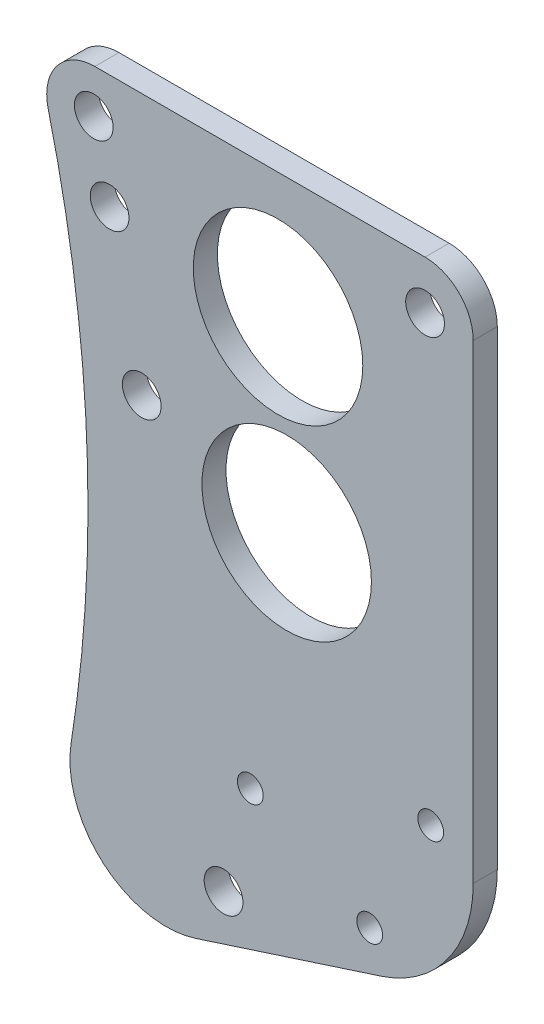
SolidWorks part; units mm, degrees
material "Polypropylene"
ref_plane "Front Plane" through (0, 0, 0) normal (0, 0, 1) x (1, 0, 0)
ref_plane "Top Plane" through (0, 0, 0) normal (0, 1, 0) x (1, 0, 0)
ref_plane "Right Plane" through (0, 0, 0) normal (1, 0, 0) x (0, 0, -1)
sketch "Sketch2" plane through (0, 0, 0) normal (0, 0, 1) x (1, 0, 0)
  line L0 (-139.7, 0) -> (139.7, 0) construction
  line L1 (-139.7, 162.1582) -> (139.7, 162.1582) construction
  line L2 (-139.7, 0) -> (-139.7, 162.1582) construction
  line L3 (89.6578, 156.3951) -> (-88.9, 111.3582) construction
  line L4 (-88.9, 111.3582) -> (87.5277, 58.5898) construction
  line L6 (85.725, 52.9003) -> (82.55, 52.9003) construction
  line L7 (139.7, 162.1582) -> (139.7, 0) construction
  line L8 (-109.7, 30) -> (-102.2692, 59.0652) construction
  line L9 (-102.2692, 59.0652) -> (-101.4828, 62.1412) construction
  line L10 (-101.4828, 62.1412) -> (-88.9, 111.3582) construction
  line L11 (-88.9, 111.3582) -> (85.725, 52.9003) construction
  line L12 (82.55, 52.9003) -> (82.55, 64.2654) construction
  line L13 (-88.9, 111.3582) -> (91.7477, 147.1022) construction
  line L14 (82.55, 52.9003) -> (85.725, 0) construction
  line L15 (85.725, 52.9003) -> (92.4089, 52.9003) construction
  line L16 (-131.5562, 154.0144) -> (-88.9, 111.3582) construction
  line L17 (-88.9, 111.3582) -> (88.9, 111.3582) construction
  line L18 (-88.9, 111.3582) -> (88.1045, 162.1582) construction
  line L22 (82.8416, 162.1582) -> (82.8416, 157.3763) construction
  line L23 (82.8416, 157.3763) -> (-88.9, 111.3582) construction
  line L24 (122.2, 93.8006) -> (115.1001, 121.5451) construction
  line L25 (-88.9, 111.3582) -> (-131.5562, 68.702) construction
  line L26 (120.5994, 121.5451) -> (117.8497, 126.3076) construction
  line L27 (117.8497, 126.3076) -> (112.3505, 126.3076) construction
  line L28 (112.3505, 126.3076) -> (109.6008, 121.5451) construction
  line L29 (109.6008, 121.5451) -> (112.3505, 116.7826) construction
  line L30 (112.3505, 116.7826) -> (117.8497, 116.7826) construction
  line L31 (117.8497, 116.7826) -> (120.5994, 121.5451) construction
  line L40 (-139.7, 154.0144) -> (-139.7, 30) construction
  line L41 (-131.5562, 161.3468) -> (-137.9062, 157.6806) construction
  line L42 (-137.9062, 157.6806) -> (-137.9062, 150.3483) construction
  line L43 (-137.9062, 150.3483) -> (-131.5562, 146.6821) construction
  line L44 (-131.5562, 146.6821) -> (-125.2062, 150.3483) construction
  line L45 (-125.2062, 150.3483) -> (-125.2062, 157.6806) construction
  line L46 (-125.2062, 157.6806) -> (-131.5562, 161.3468) construction
  line L47 (-131.5562, 61.3697) -> (-125.2062, 65.0358) construction
  line L48 (-125.2062, 65.0358) -> (-125.2062, 72.3682) construction
  line L49 (-125.2062, 72.3682) -> (-131.5562, 76.0344) construction
  line L50 (-131.5562, 76.0344) -> (-137.9062, 72.3682) construction
  line L51 (-137.9062, 72.3682) -> (-137.9062, 65.0358) construction
  line L52 (-137.9062, 65.0358) -> (-131.5562, 61.3697) construction
  line L53 (-79.9907, 25.8335) -> (-68.3996, 108.4832) construction
  line L54 (-77.6298, 128.7224) -> (-127.1225, 160.8455) construction
  line L56 (89.8048, 162.1582) -> (133.35, 162.1582)
  line L57 (139.7, 155.8082) -> (139.7, 93.8006)
  line L58 (127.5896, 77.1512) -> (103.1274, 69.2325)
  line L59 (137.8401, 160.2984) -> (129.3001, 151.7583) construction
  line L60 (122.2, 93.8006) -> (110.579, 80.7162) construction
  line L61 (110.579, 80.7162) -> (106.7754, 76.4337) construction
  line L62 (98.6364, 77.8864) -> (101.1368, 77.4401) construction
  line L63 (98.6364, 77.8864) -> (-88.9, 111.3582) construction
  line L64 (106.7754, 76.4337) -> (108.5394, 70.9844) construction
  line L65 (113.9624, 145.6482) -> (95.9884, 127.7012) construction
  line L66 (115.1001, 121.5451) -> (104.4623, 124.9716) construction
  line L67 (95.9884, 127.7012) -> (98.4182, 126.9185) construction
  line L68 (98.4182, 126.9185) -> (104.4623, 124.9716) construction
  line L69 (101.1368, 77.4401) -> (106.7754, 76.4337) construction
  circle A0 centre (-88.9, 111.3582) radius 50.8 construction
  circle A1 centre (-88.9, 111.3582) radius 14.351 construction
  arc A15 (81.4439, 60.4094) -> (81.4884, 162.1582) centre (-88.9, 111.3582) ccw construction
  arc A16 (92.4089, 52.9003) -> (94.7018, 162.1582) centre (-88.9, 111.3582) ccw construction
  arc A17 (89.6578, 156.3951) -> (87.5277, 58.5898) centre (-88.9, 111.3582) cw construction
  arc A18 (90.2045, 57.7892) -> (92.367, 157.0784) centre (-88.9, 111.3582) ccw construction
  arc A19 (84.8508, 59.3905) -> (86.9487, 155.7118) centre (-88.9, 111.3582) ccw construction
  arc A20 (84.8508, 59.3905) -> (90.2045, 57.7892) centre (87.5277, 58.5898) ccw construction
  arc A21 (92.367, 157.0784) -> (86.9487, 155.7118) centre (89.6578, 156.3951) ccw construction
  arc A23 (89.6578, 156.3951) -> (88.1045, 162.1582) centre (-88.9, 111.3582) ccw construction
  circle A24 centre (113.9624, 145.6482) radius 15.24 construction
  circle A25 centre (122.2, 93.8006) radius 17.5 construction
  circle A26 centre (122.2, 93.8006) radius 4.826 construction
  circle A27 centre (115.1001, 121.5451) radius 23.8125 construction
  circle A28 centre (113.9624, 145.6482) radius 16.51 construction
  circle A29 centre (-109.7, 30) radius 30 construction
  circle A30 centre (-109.7, 30) radius 25.4 construction
  circle A31 centre (-109.7, 55.4) radius 2.5527 construction
  circle A32 centre (-97, 51.997) radius 2.5527 construction
  circle A33 centre (-87.703, 42.7) radius 2.5527 construction
  circle A34 centre (-84.3, 30) radius 2.5527 construction
  circle A35 centre (-87.703, 17.3) radius 2.5527 construction
  circle A36 centre (-97, 8.003) radius 2.5527 construction
  circle A37 centre (-109.7, 4.6) radius 2.5527 construction
  circle A38 centre (-122.4, 8.003) radius 2.5527 construction
  circle A39 centre (-131.697, 17.3) radius 2.5527 construction
  circle A40 centre (-135.1, 30) radius 2.5527 construction
  circle A41 centre (-131.697, 42.7) radius 2.5527 construction
  circle A42 centre (-122.4, 51.997) radius 2.5527 construction
  arc A43 (87.5277, 58.5898) -> (85.725, 52.9003) centre (-88.9, 111.3582) cw construction
  circle A44 centre (-109.7, 30) radius 14.351 construction
  circle A48 centre (115.1001, 121.5451) radius 24.5999 construction
  circle A49 centre (122.2, 93.8006) radius 12.5 construction
  circle A50 centre (134.0938, 97.6461) radius 1.25 construction
  circle A51 centre (126.0455, 81.9068) radius 1.25 construction
  circle A52 centre (110.3062, 89.9551) radius 1.25 construction
  circle A53 centre (118.3545, 105.6944) radius 1.25 construction
  circle A54 centre (115.1001, 121.5451) radius 4.7625 construction
  circle A55 centre (115.1001, 121.5451) radius 8.89 construction
  circle A56 centre (115.1001, 121.5451) radius 10.16 construction
  circle A59 centre (113.9624, 145.6482) radius 15.24 construction
  circle A60 centre (113.9624, 145.6482) radius 16.51 construction
  circle A61 centre (89.6578, 156.3951) radius 2.5527
  circle A62 centre (91.7477, 147.1022) radius 2.5527
  circle A63 centre (-131.5562, 68.702) radius 3.175 construction
  circle A64 centre (-131.5562, 154.0144) radius 3.175 construction
  circle A65 centre (-131.5562, 154.0144) radius 6.35 construction
  circle A66 centre (-131.5562, 68.702) radius 6.35 construction
  arc A67 (-139.7, 30) -> (-79.9907, 25.8335) centre (-109.7, 30) ccw construction
  arc A69 (-127.1225, 160.8455) -> (-139.7, 154.0144) centre (-131.5562, 154.0144) ccw construction
  arc A70 (-68.3996, 108.4832) -> (-77.6298, 128.7224) centre (-88.9, 111.3582) ccw construction
  arc A71 (139.7, 93.8006) -> (127.5896, 77.1512) centre (122.2, 93.8006) cw
  arc A72 (83.6426, 154.2755) -> (86.675, 83.318) centre (-88.9, 111.3582) cw
  arc A73 (86.675, 83.318) -> (103.1274, 69.2325) centre (99.2161, 81.3152) ccw
  arc A74 (133.35, 162.1582) -> (139.7, 155.8082) centre (133.35, 155.8082) cw
  circle A76 centre (106.7754, 76.4337) radius 2.5527
  arc A77 (110.3062, 89.9551) -> (134.0938, 97.6461) centre (122.2, 93.8006) ccw construction
  arc A78 (106.0958, 88.5937) -> (138.3042, 99.0075) centre (122.2, 93.8006) ccw construction
  arc A79 (114.5166, 91.3164) -> (129.8834, 96.2848) centre (122.2, 93.8006) ccw construction
  arc A80 (114.5166, 91.3164) -> (106.0958, 88.5937) centre (110.3062, 89.9551) ccw construction
  arc A81 (138.3042, 99.0075) -> (129.8834, 96.2848) centre (134.0938, 97.6461) ccw construction
  circle A82 centre (115.1001, 121.5451) radius 11.176
  arc A83 (83.6426, 154.2755) -> (89.8048, 162.1582) centre (89.8048, 155.8082) cw
  circle A84 centre (113.9624, 145.6482) radius 11.176
  circle A87 centre (133.35, 155.8082) radius 2.5527
  circle A88 centre (95.9884, 127.7012) radius 2.5527
  circle A89 centre (134.0938, 97.6461) radius 1.7
  circle A90 centre (126.0455, 81.9068) radius 1.7
  circle A91 centre (110.3062, 89.9551) radius 1.7
  point P6 (-88.9, 60.5582)
  point P10 (-109.7, 0)
  point P11 (86.727, 55.913)
  point P30 (-88.9, 111.3582)
  point P32 (0, 0)
  point P36 (0, 162.1582)
  point P37 (-88.9, 162.1582)
  point P42 (95.2063, 107.3484)
  point P66 (-109.7, 30)
  point P68 (-139.7, 30)
  point P82 (88.954, 159.099)
  point P85 (-79.7, 30)
  point P92 (88.1045, 162.1582)
  point P105 (122.2, 93.8006)
  point P138 (132.0087, 101.5491)
  point P142 (107.5616, 74.0051)
  point P148 (126.0455, 81.9068)
  point P171 (130.9475, 102.7298)
  dimension "D1" = 101.6
  dimension "D2" = 28.702
  dimension "D3" = 60
  dimension "D4" = 50.8
  dimension "D9" = 127
  dimension "D10" = 12.7
  dimension "D11" = 6.35
  dimension "D12" = 2.794
  dimension "D16" = 35
  dimension "D17" = 9.652
  dimension "D18" = 47.625
  dimension "D19" = 30.48
  dimension "D20" = 30.48
  dimension "D5" = 5.1054
  dimension "D13" = 85.725
  dimension "D25" = 28.702
  dimension "D21" = 82.55
  dimension "D22" = 186.944
  dimension "D30" = 49.1998
  dimension "D31" = 60.325
  dimension "D32" = 27.844
  dimension "D33" = 12.7
  dimension "D34" = 25
  dimension "D35" = 2.5
  dimension "D37" = 9.525
  dimension "D38" = 17.78
  dimension "D39" = 20.32
  dimension "D40" = 6.35
  dimension "D41" = 6.35
  dimension "D42" = 1.27
  dimension "D43" = 1.27
  dimension "D44" = 12.7
  dimension "D45" = 3.175
  dimension "D46" = 3.175
  dimension "D28" = 5.1054
  dimension "D29" = 6.35
  dimension "D47" = 22.352
  dimension "D48" = 6.35
  dimension "D49" = 22.352
  dimension "D52" = 25.4
  dimension "D53" = 5.1054
  dimension "D51" = 5.1054
  dimension "D55" = 2.54
  dimension "D56" = 1.5875
  dimension "D57" = 3.4
  dimension "D6" = 12
  dimension "D7" = 15
  dimension "D8" = 279.4
  dimension "D14" = 3.175
  dimension "D15" = 279.4
  dimension "D23" = 3.175
  dimension "D24" = 3.175
  dimension "D26" = 3.175
  dimension "D27" = 9.525
  dimension "D50" = 12.0774
  dimension "D54" = 6.35
  dimension "D36" = 4
extrude "Boss-Extrude1" add sketch "Sketch2" along normal blind 3.175
